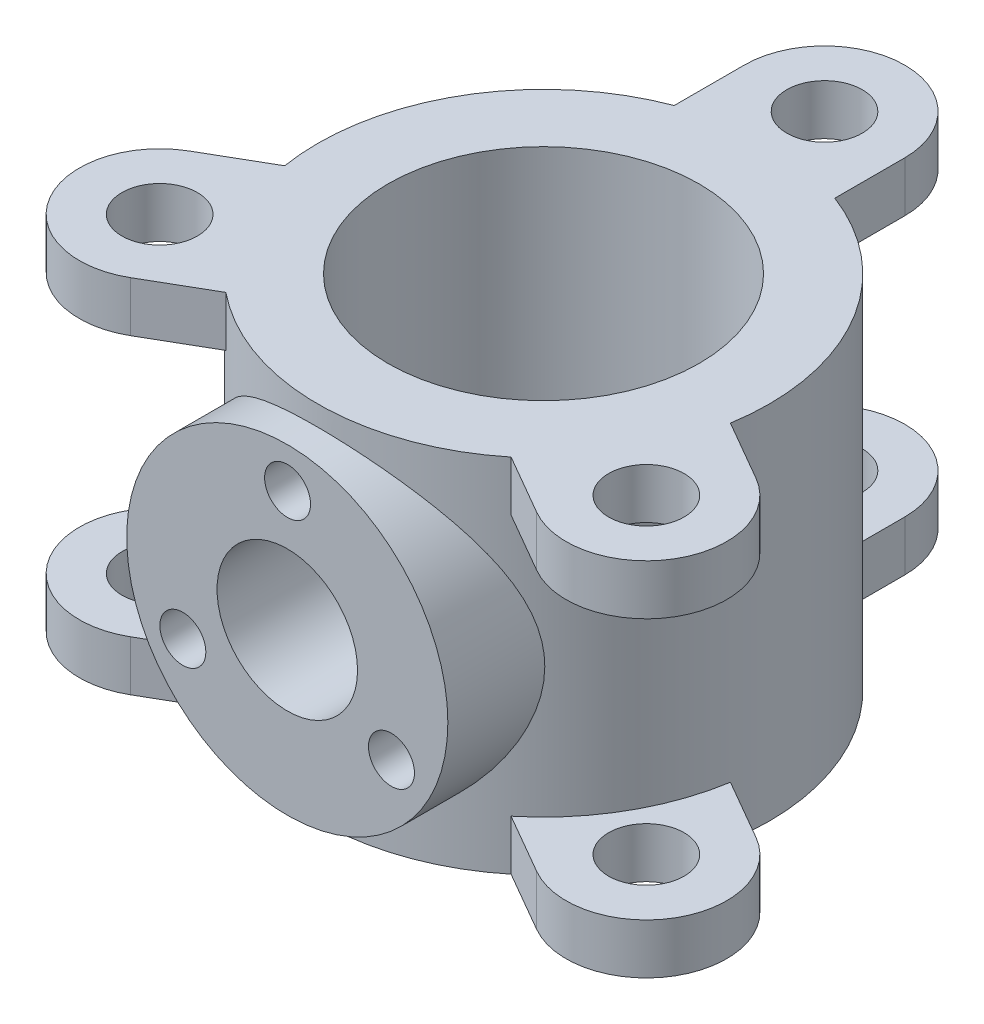
SolidWorks part; units mm, degrees
ref_plane "Front Plane" through (0, 0, 0) normal (0, 0, 1) x (1, 0, 0)
ref_plane "Top Plane" through (0, 0, 0) normal (0, 1, 0) x (1, 0, 0)
ref_plane "Right Plane" through (0, 0, 0) normal (1, 0, 0) x (0, 0, -1)
sketch "Sketch1" plane through (0, 0, 0) normal (0, 1, 0) x (1, 0, 0)
  circle A0 centre (0, 0) radius 24.6126
  circle A1 centre (0, 0) radius 35.7124
  dimension "D1" = 49.2252
  dimension "D2" = 71.4248
extrude "Boss-Extrude1" add sketch "Sketch1" along normal blind 57.15
sketch "Sketch2" plane through (0, 57.15, 0) normal (0, 1, 0) x (1, 0, 0)
  line L0 (0, 0) -> (0, 44.45) construction
  line L1 (-12.7, 44.45) -> (-12.7, 33.3779)
  line L2 (12.7, 44.45) -> (12.7, 33.3779)
  line L3 (-12.7, 33.3779) -> (12.7, 33.3779)
  circle A1 centre (0, 44.45) radius 5.969
  arc A2 (-12.7, 44.45) -> (12.7, 44.45) centre (0, 44.45) cw
  circle A3 centre (0, 0) radius 35.7124 construction
  dimension "D2" = 11.938
  dimension "D3" = 12.7
  dimension "D1" = 44.45
extrude "Boss-Extrude2" add sketch "Sketch2" against normal blind 7.9502
pattern_circular "CirPattern1" count 3 over 360 about axis through (0, 0, 0) along (0, 1, 0) of "Boss-Extrude2"
ref_plane "Plane1" through (0, 28.575, 0) normal (0, 1, 0) x (1, 0, 0)
mirror "Mirror1" about plane through (0, 28.575, 0) normal (0, 1, 0) of "CirPattern1", "Boss-Extrude2"
ref_plane "Plane2" through (0, 0, 40.4876) normal (0, 0, 1) x (1, 0, 0)
sketch "Sketch3" plane through (0, 0, 40.4876) normal (0, 0, 1) x (1, 0, 0)
  line L0 (22.5561, 57.15) -> (-22.5561, 57.15) construction
  circle A0 centre (-0.0444, 28.575) radius 25.4
  dimension "D2" = 50.8
  dimension "D1" = 28.575
extrude "Boss-Extrude3" add sketch "Sketch3" against normal blind 19.05
sketch "Sketch4" plane through (0, 57.15, 0) normal (0, 1, 0) x (1, 0, 0)
  circle A0 centre (0, 0) radius 24.6126
extrude "Cut-Extrude1" cut sketch "Sketch4" against normal blind 57.15
sketch "Sketch6" plane through (0, 0, 40.4876) normal (0, 0, 1) x (1, 0, 0)
  circle A0 centre (-0.0444, 28.575) radius 11.1125
  dimension "D1" = 22.225
extrude "Cut-Extrude2" cut sketch "Sketch6" against normal blind 57.15
sketch "Sketch7" plane through (0, 0, 40.4876) normal (0, 0, 1) x (1, 0, 0)
  circle A0 centre (0, 47.625) radius 3.636
  circle A2 centre (16.4312, 19.0116) radius 3.636
  circle A3 centre (-16.5644, 19.0884) radius 3.636
  point P10 (-0.0444, 28.575)
  dimension "D2" = 3
  dimension "D1" = 19.05
extrude "Cut-Extrude3" cut sketch "Sketch7" against normal blind 9.525
